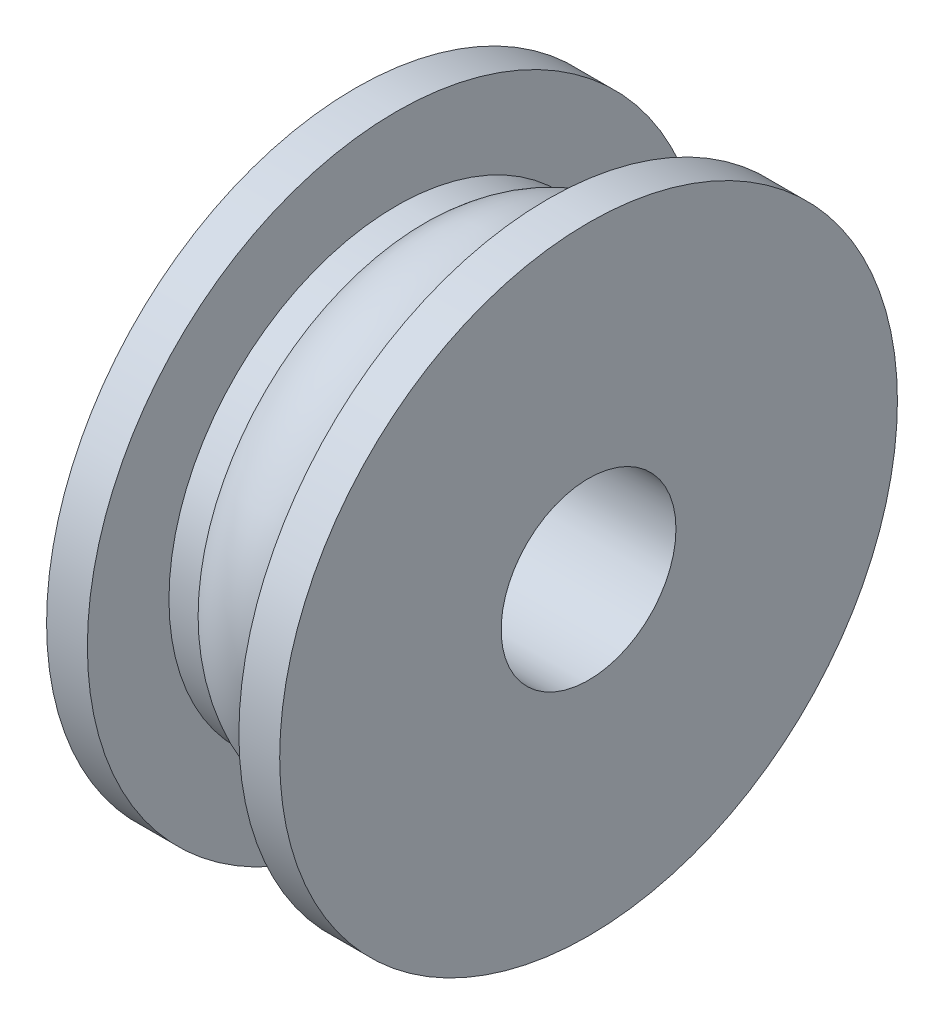
SolidWorks part; units mm, degrees
ref_plane "Front Plane" through (0, 0, 0) normal (0, 0, 1) x (1, 0, 0)
ref_plane "Top Plane" through (0, 0, 0) normal (0, 1, 0) x (1, 0, 0)
ref_plane "Right Plane" through (0, 0, 0) normal (1, 0, 0) x (0, 0, -1)
sketch "Sketch1" plane through (0, 0, 0) normal (0, 0, 1) x (1, 0, 0)
  line L0 (0, 0) -> (2, 0)
  line L1 (2, 0) -> (2, 5.3)
  line L2 (2, 5.3) -> (1.3, 5.3)
  line L3 (-2, 5.3) -> (-2, 0)
  line L4 (-2, 0) -> (0, 0)
  line L5 (-1.3, 5.3) -> (-1.3, 3.9)
  line L6 (-1.3, 3.9) -> (-0.8, 3.9)
  line L7 (1.3, 5.3) -> (1.3, 3.9)
  line L8 (1.3, 3.9) -> (0.8, 3.9)
  line L9 (-1.3, 5.3) -> (-2, 5.3)
  arc A0 (-0.8, 3.9) -> (0.8, 3.9) centre (0, 2.9964) cw
  dimension "D1" = 2
  dimension "D2" = 5.3
  dimension "D3" = 2
  dimension "D4" = 3.9
  dimension "D5" = 2.6
  dimension "D6" = 1.3
  dimension "D7" = 0.5
  dimension "D8" = 0.5
revolve "Revolve1" add sketch "Sketch1" angle 360 about L0
sketch "Sketch2" plane through (2, 0, 0) normal (1, 0, 0) x (0, 0, -1)
  circle A0 centre (0, 0) radius 1.5
  dimension "D1" = 3
extrude "Cut-Extrude1" cut sketch "Sketch2" against normal through all
